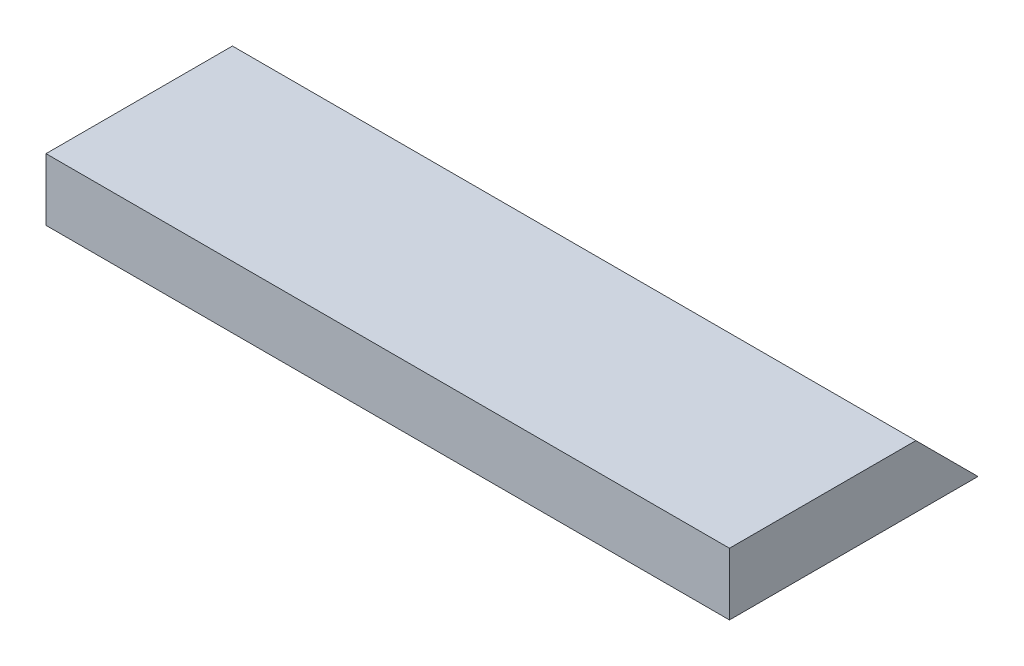
SolidWorks part; units mm, degrees
material "Pure Gold"
ref_plane "Front Plane" through (0, 0, 0) normal (0, 0, 1) x (1, 0, 0)
ref_plane "Top Plane" through (0, 0, 0) normal (0, 1, 0) x (1, 0, 0)
ref_plane "Right Plane" through (0, 0, 0) normal (1, 0, 0) x (0, 0, -1)
sketch "Sketch1" plane through (0, 0, 0) normal (0, 1, 0) x (1, 0, 0)
  line L1 (0, 0) -> (-55, 0)
  line L2 (0, 0) -> (0, 20)
  line L3 (0, 20) -> (-55, 20)
  line L4 (-55, 0) -> (-55, 20)
  dimension "D1" = 20
  dimension "D2" = 55
extrude "Boss-Extrude1" add sketch "Sketch1" along normal blind 5
sketch "Sketch6" plane through (-55, 0, 0) normal (-1, 0, 0) x (0, 0, 1)
  line L0 (-20, 0) -> (-15, 5)
  line L1 (-20, 5) -> (0, 5) construction
  line L2 (-15, 5) -> (-20, 5)
  line L3 (-20, 5) -> (-20, 0)
extrude "Cut-Extrude3" cut sketch "Sketch6" against normal up to next
